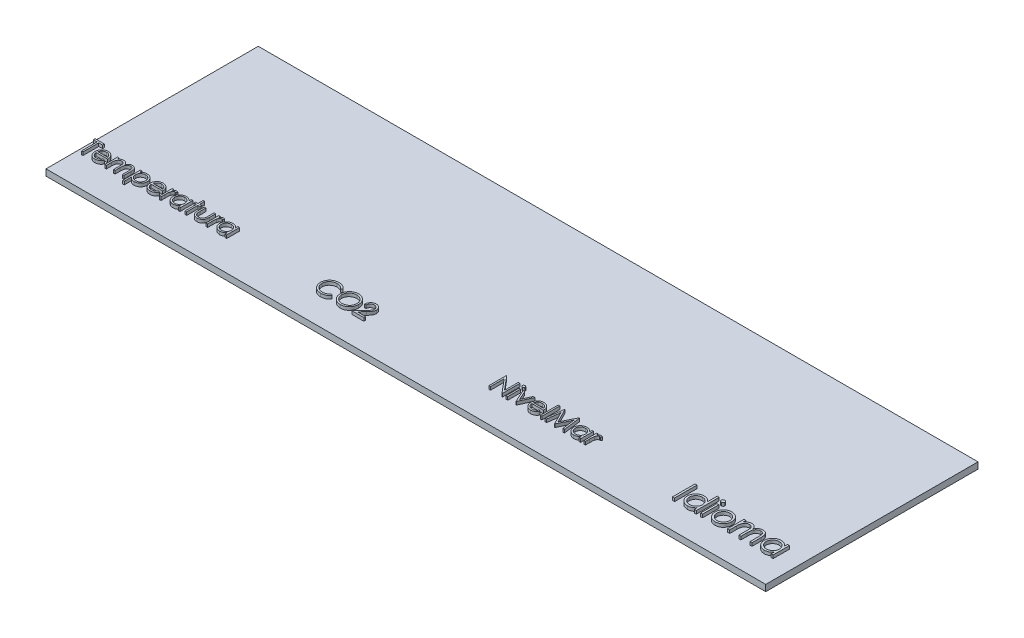
SolidWorks part; units mm, degrees
ref_plane "Alzado" through (0, 0, 0) normal (0, 0, 1) x (1, 0, 0)
ref_plane "Planta" through (0, 0, 0) normal (0, 1, 0) x (1, 0, 0)
ref_plane "Vista lateral" through (0, 0, 0) normal (1, 0, 0) x (0, 0, -1)
sketch "Croquis1" plane through (0, 0, 0) normal (0, 1, 0) x (1, 0, 0)
  line L1 (-113, -33.325) -> (113, -33.325)
  line L2 (-113, -33.325) -> (-113, 33.325)
  line L3 (-113, 33.325) -> (113, 33.325)
  line L4 (113, -33.325) -> (113, 33.325)
  line L5 (-113, -33.325) -> (113, 33.325) construction
  line L6 (-113, 33.325) -> (113, -33.325) construction
  point P0 (0, 0)
  dimension "D1" = 226
  dimension "D2" = 66.65
extrude "Saliente-Extruir1" add sketch "Croquis1" along normal blind 2
sketch "Croquis4" plane through (0, 2, 0) normal (0, 1, 0) x (1, 0, 0)
  text T0 "Temperatura" font "Century Gothic" height 5.5
extrude "Saliente-Extruir3" add sketch "Croquis4" along normal blind 1
sketch "Croquis5" plane through (0, 2, 0) normal (0, 1, 0) x (1, 0, 0)
  text T0 "CO2" font "Century Gothic" height 5.5
extrude "Saliente-Extruir4" add sketch "Croquis5" along normal blind 1
sketch "Croquis6" plane through (0, 2, 0) normal (0, 1, 0) x (1, 0, 0)
  text T0 "NivelMar" font "Century Gothic" height 5.5
extrude "Saliente-Extruir5" add sketch "Croquis6" along normal blind 1
sketch "Croquis7" plane through (0, 2, 0) normal (0, 1, 0) x (1, 0, 0)
  text T0 "Idioma" font "Century Gothic" height 7
extrude "Saliente-Extruir6" add sketch "Croquis7" along normal blind 1
